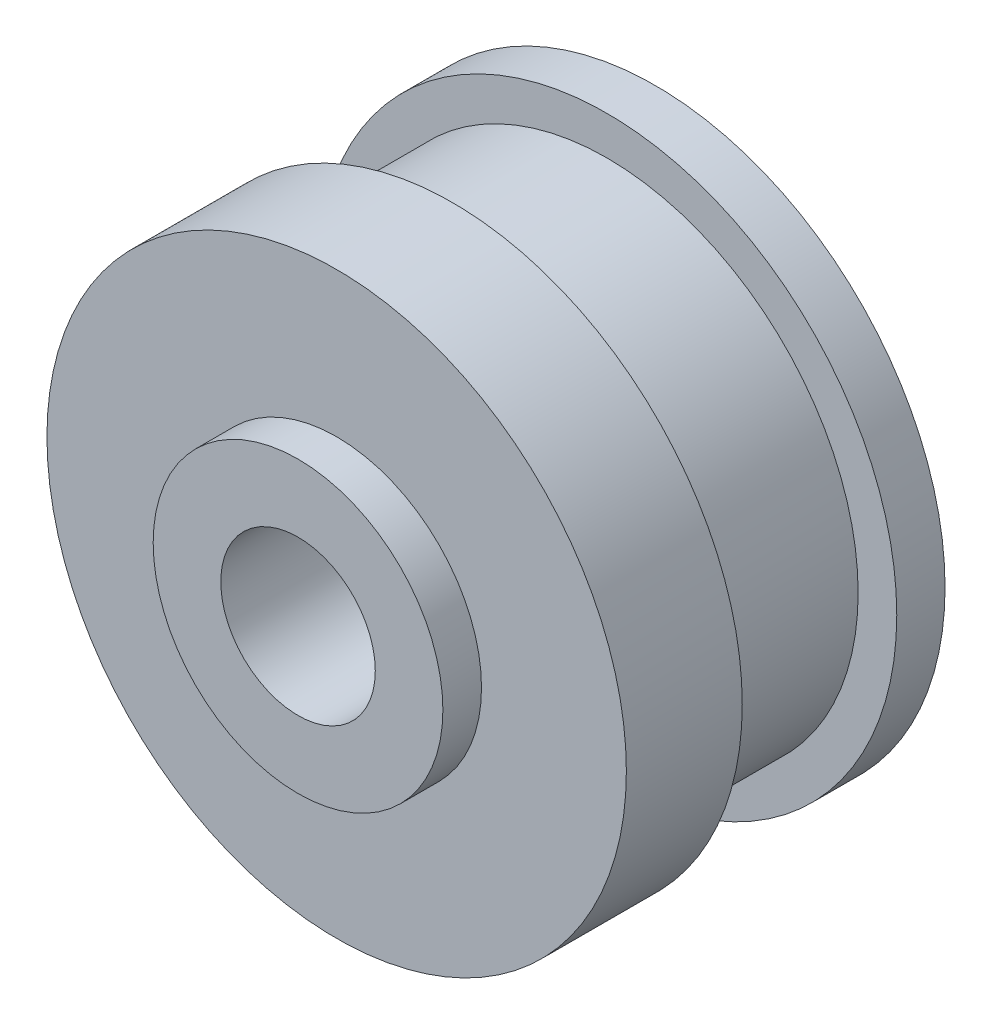
SolidWorks part; units mm, degrees
ref_plane "Ebene vorne" through (0, 0, 0) normal (1, 0, 0) x (0, 1, 0)
ref_plane "Ebene oben" through (0, 0, 0) normal (0, 0, 1) x (0, 1, 0)
ref_plane "Ebene rechts" through (0, 0, 0) normal (0, 1, 0) x (-1, 0, 0)
sketch "Skizze1" plane through (0, 0, 0) normal (0, 0, 1) x (0, 1, 0)
  circle A0 centre (0, 0) radius 15
  dimension "D1" = 30
extrude "Aufsatz-Linear austragen1" add sketch "Skizze1" along normal blind 16.5
sketch "Skizze2" plane through (0, 0, 16.5) normal (0, 0, 1) x (1, 0, 0)
  circle A0 centre (0, 0) radius 4
  dimension "D1" = 8
extrude "Schnitt-Linear austragen1" cut sketch "Skizze2" against normal up to next
sketch "Skizze3" plane through (0, 0, 0) normal (0, 1, 0) x (-1, 0, 0)
  line L0 (-15, 10.5) -> (-13, 10.5)
  line L1 (-13, 10.5) -> (-13, 2.5)
  line L2 (-13, 2.5) -> (-15, 2.5)
  line L3 (-15, 2.5) -> (-15, 10.5)
  line L4 (0, 0) -> (0, 17.8816) construction
  line L5 (-15, 16.5) -> (-15, 0) construction
  line L6 (-15, 0) -> (15, 0) construction
  dimension "D1" = 2
  dimension "D2" = 8
  dimension "D3" = 2.5
sketch "Skizze4" plane through (0, 0, 16.5) normal (0, 0, 1) x (1, 0, 0)
  circle A0 centre (0, 0) radius 7.5
  circle A1 centre (0, 0) radius 4
  circle A2 centre (0, 0) radius 4 construction
  dimension "D1" = 15
extrude "Aufsatz-Linear austragen2" add sketch "Skizze4" along normal blind 2
revolve "Schnitt-Rotation1" cut sketch "Skizze3" angle 360 about L4
